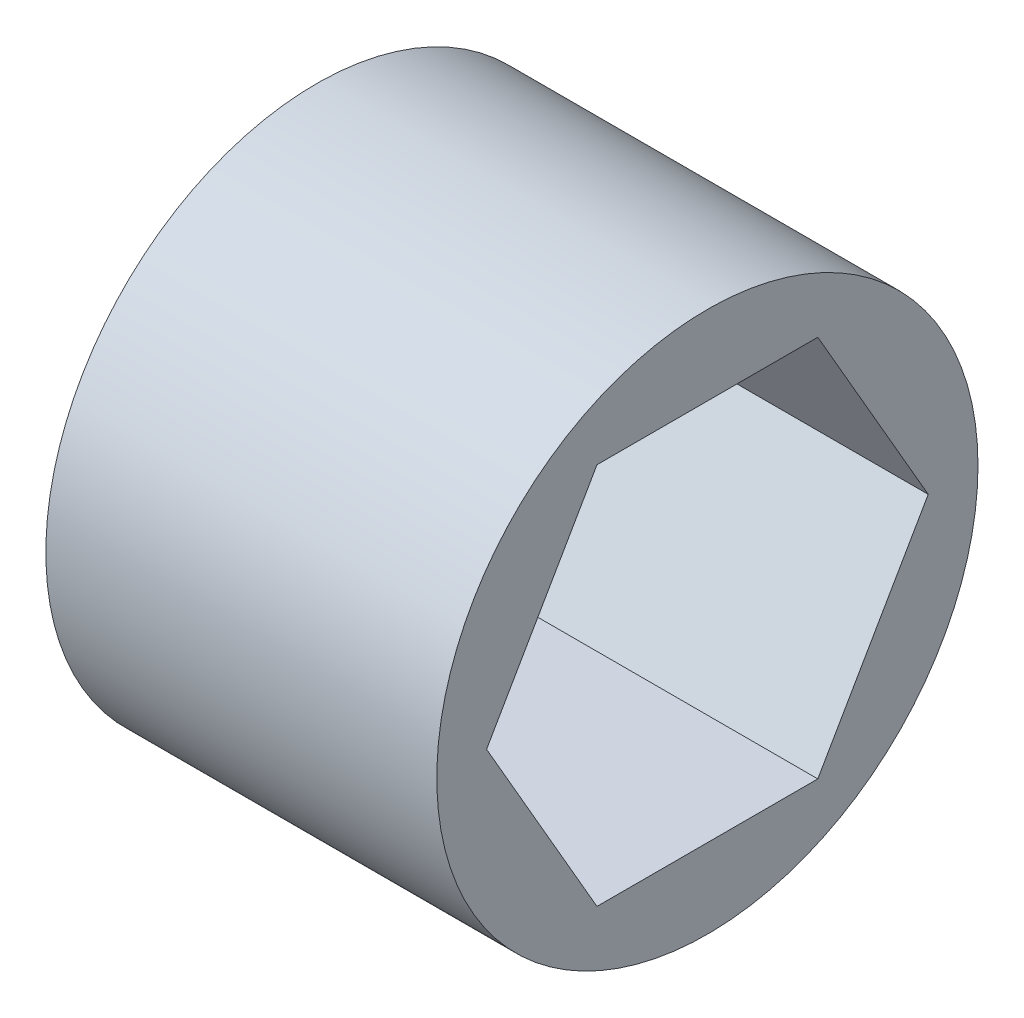
SolidWorks part; units mm, degrees
ref_plane "Front Plane" through (0, 0, 0) normal (0, 0, 1) x (1, 0, 0)
ref_plane "Top Plane" through (0, 0, 0) normal (0, 1, 0) x (1, 0, 0)
ref_plane "Right Plane" through (0, 0, 0) normal (1, 0, 0) x (0, 0, -1)
sketch "Sketch1" plane through (0, 0, 0) normal (1, 0, 0) x (0, 0, -1)
  line L1 (7.7723, 0) -> (3.8861, 6.731)
  line L2 (3.8861, 6.731) -> (-3.8861, 6.731)
  line L3 (-3.8861, 6.731) -> (-7.7723, 0)
  line L4 (-7.7723, 0) -> (-3.8861, -6.731)
  line L5 (-3.8861, -6.731) -> (3.8861, -6.731)
  line L6 (3.8861, -6.731) -> (7.7723, 0)
  circle A0 centre (0, 0) radius 6.731 construction
  circle A1 centre (0, 0) radius 9.525
  dimension "D1" = 13.462
  dimension "D2" = 19.05
extrude "Boss-Extrude1" add sketch "Sketch1" along normal blind 13.7604
